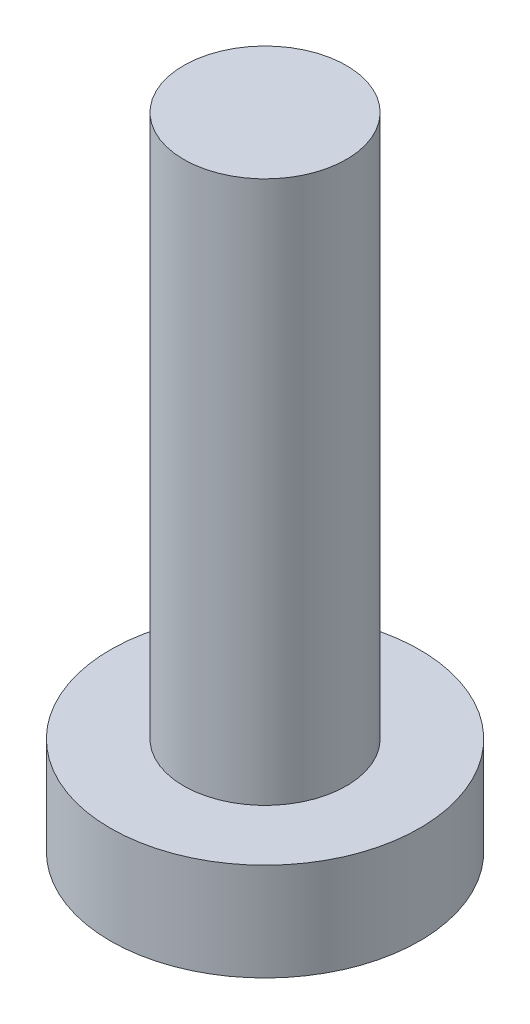
SolidWorks part; units mm, degrees
material "AISI 304"
ref_plane "前视基准面" through (0, 0, 0) normal (0, 0, 1) x (1, 0, 0)
ref_plane "上视基准面" through (0, 0, 0) normal (0, 1, 0) x (1, 0, 0)
ref_plane "右视基准面" through (0, 0, 0) normal (1, 0, 0) x (0, 0, -1)
sketch "草图1" plane through (0, 0, 0) normal (0, 0, 1) x (1, 0, 0)
  line L0 (0, 5.0793) -> (0, -4.5921) construction
  line L1 (-4.7636, 0) -> (5.5214, 0) construction
  line L2 (0, 0) -> (2.85, 0)
  line L3 (2.85, 0) -> (2.85, 1.8)
  line L4 (2.85, 1.8) -> (1.5, 1.8)
  line L5 (1.5, 1.8) -> (1.5, 11.8)
  line L6 (1.5, 11.8) -> (0, 11.8)
  line L7 (0, 11.8) -> (0, 0)
  dimension "D1" = 3
  dimension "D2" = 5.7
  dimension "D3" = 1.8
  dimension "D4" = 10
revolve "旋转1" add sketch "草图1" angle 360 about L0
sketch "草图2" plane through (0, 0, 0) normal (0, -1, 0) x (1, 0, 0)
  line L1 (0, -1.425) -> (1.2341, -0.7125)
  line L2 (1.2341, -0.7125) -> (1.2341, 0.7125)
  line L3 (1.2341, 0.7125) -> (0, 1.425)
  line L4 (0, 1.425) -> (-1.2341, 0.7125)
  line L5 (-1.2341, 0.7125) -> (-1.2341, -0.7125)
  line L6 (-1.2341, -0.7125) -> (0, -1.425)
  circle A0 centre (0, 0) radius 1.425 construction
  dimension "D1" = 2.85
extrude "切除-拉伸1" cut sketch "草图2" against normal blind 1.5
equation "\"长度\"= 10"
equation "\"螺钉头直径\"= 5.7"
equation "\"螺钉直径\"= 3"
equation "\"螺钉头厚度\"= 1.8"
equation "\"D1@草图1\"= \"螺钉直径\""
equation "\"D2@草图1\"= \"螺钉头直径\""
equation "\"D3@草图1\"= \"螺钉头厚度\""
equation "\"D4@草图1\"= \"长度\""
equation "\"D1@草图2\"= \"螺钉头直径\" * 0.5"
